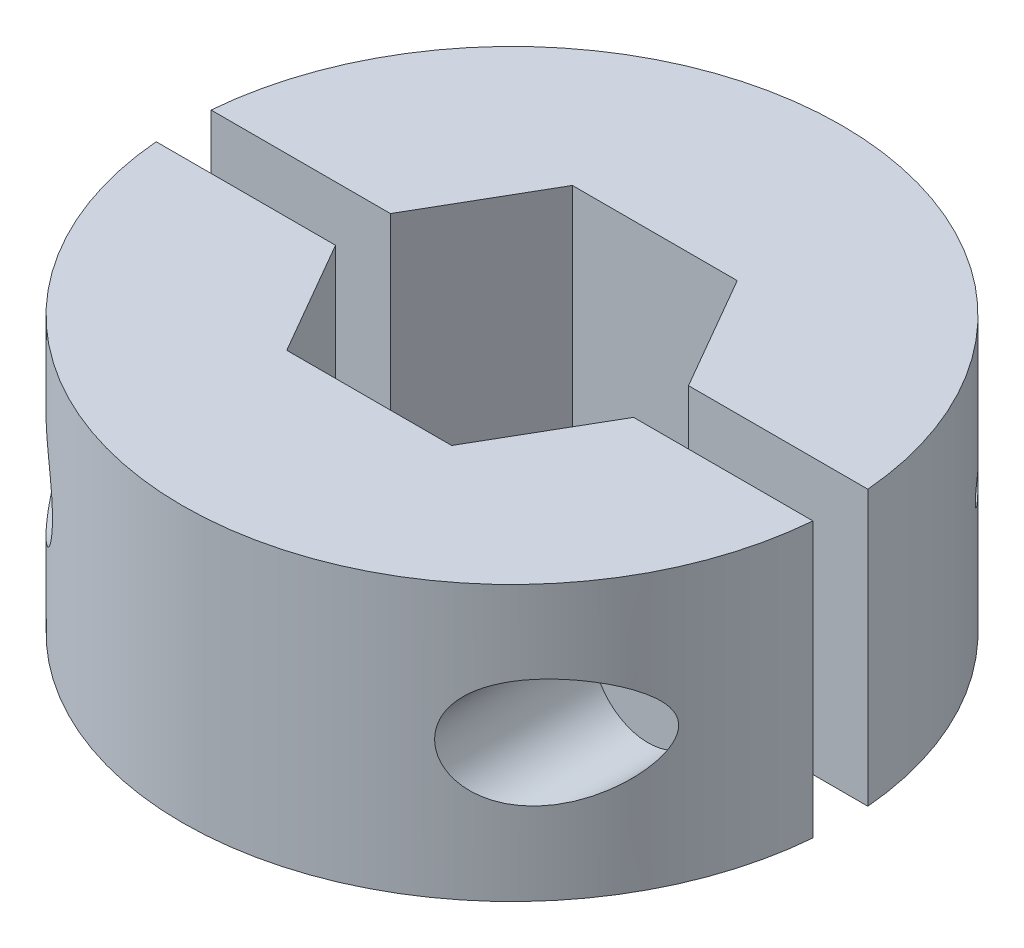
SolidWorks part; units mm, degrees
ref_plane "Front Plane" through (0, 0, 0) normal (0, 0, 1) x (1, 0, 0)
ref_plane "Top Plane" through (0, 0, 0) normal (0, 1, 0) x (1, 0, 0)
ref_plane "Right Plane" through (0, 0, 0) normal (1, 0, 0) x (0, 0, -1)
sketch "Sketch1" plane through (0, 0, 0) normal (0, 1, 0) x (1, 0, 0)
  circle A0 centre (0, 0) radius 15.24
  dimension "D1" = 30.48
extrude "Boss-Extrude1" add sketch "Sketch1" along normal blind 12.7
sketch "Sketch2" plane through (0, 12.7, 0) normal (0, 1, 0) x (1, 0, 0)
  line L1 (7.6256, 0) -> (3.8128, 6.604)
  line L2 (3.8128, 6.604) -> (-3.8128, 6.604)
  line L3 (-3.8128, 6.604) -> (-7.6256, 0)
  line L4 (-7.6256, 0) -> (-3.8128, -6.604)
  line L5 (-3.8128, -6.604) -> (3.8128, -6.604)
  line L6 (3.8128, -6.604) -> (7.6256, 0)
  circle A0 centre (0, 0) radius 6.604 construction
extrude "Cut-Extrude1" cut sketch "Sketch2" against normal blind 12.7
sketch "Sketch3" plane through (0, 12.7, 0) normal (0, 1, 0) x (1, 0, 0)
  line L3 (-15.24, 0) -> (-15.24, -1.27)
  line L4 (-15.24, -1.27) -> (15.24, -1.27)
  line L5 (15.24, 0) -> (15.24, -1.27)
  line L7 (-15.24, 0) -> (-15.24, 1.27)
  line L8 (-15.24, 1.27) -> (15.24, 1.27)
  line L9 (15.24, 0) -> (15.24, 1.27)
  circle A0 centre (0, 0) radius 15.24 construction
  dimension "D1" = 1.27
  dimension "D2" = 1.27
extrude "Cut-Extrude2" cut sketch "Sketch3" against normal blind 12.7
ref_plane "Plane1" through (0, 0, 15.24) normal (0, 0, 1) x (1, 0, 0)
sketch "Sketch4" plane through (0, 0, 15.24) normal (0, 0, 1) x (1, 0, 0)
  line L0 (15.187, 0) -> (15.187, 12.7) construction
  line L1 (-15.187, 12.7) -> (-15.187, 0) construction
  circle A0 centre (-11.377, 6.35) radius 2.54
  circle A1 centre (11.377, 6.35) radius 2.54
  dimension "D1" = 5.08
  dimension "D2" = 5.08
  dimension "D3" = 3.81
  dimension "D4" = 3.81
extrude "Cut-Extrude3" cut sketch "Sketch4" against normal blind 10.16
sketch "Sketch5" plane through (0, 0, 5.08) normal (0, 0, 1) x (1, 0, 0)
  circle A0 centre (-11.377, 6.35) radius 0.508
  circle A1 centre (11.377, 6.35) radius 0.508
  dimension "D1" = 1.016
  dimension "D2" = 1.016
extrude "Cut-Extrude4" cut sketch "Sketch5" against normal through all
